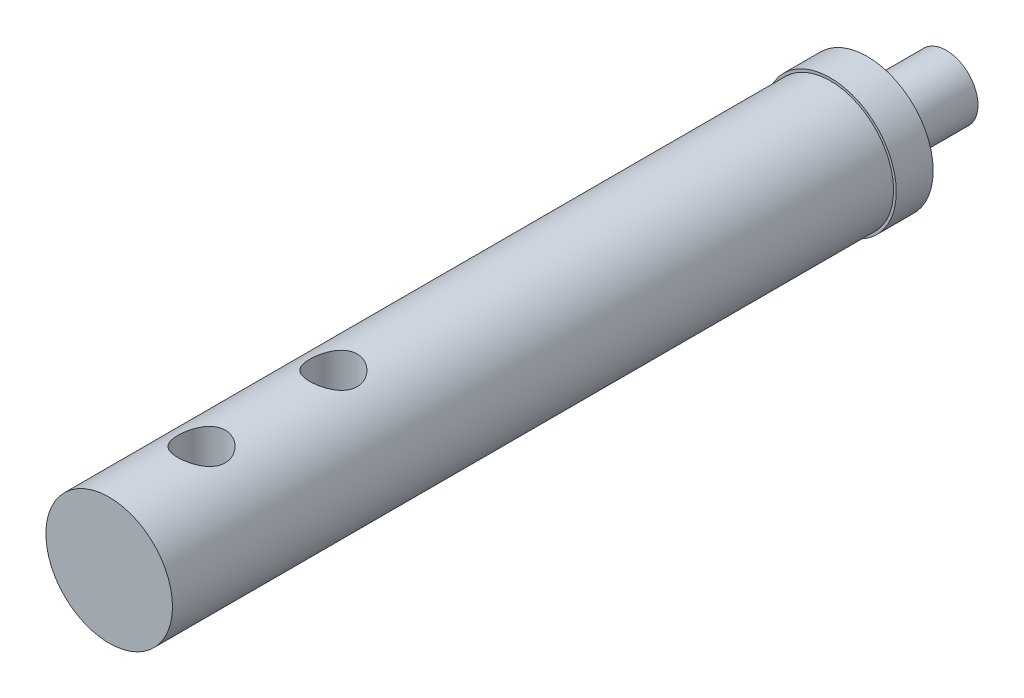
SolidWorks part; units mm, degrees
material "Galvanized Steel"
ref_plane "Front Plane" through (0, 0, 0) normal (0, 0, 1) x (1, 0, 0)
ref_plane "Top Plane" through (0, 0, 0) normal (0, 1, 0) x (1, 0, 0)
ref_plane "Right Plane" through (0, 0, 0) normal (1, 0, 0) x (0, 0, -1)
sketch "Sketch1" plane through (0, 0, 0) normal (0, 0, 1) x (1, 0, 0)
  circle A0 centre (0, 0) radius 6
  dimension "D1" = 12
extrude "Boss-Extrude1" add sketch "Sketch1" along normal blind 15
sketch "Sketch2" plane through (0, 0, 15) normal (0, 0, 1) x (1, 0, 0)
  circle A0 centre (0, 0) radius 12.5
  dimension "D1" = 25
extrude "Boss-Extrude2" add sketch "Sketch2" along normal blind 7
sketch "Sketch3" plane through (0, 0, 22) normal (0, 0, 1) x (1, 0, 0)
  circle A0 centre (0, 0) radius 12
  dimension "D1" = 24
extrude "Boss-Extrude3" add sketch "Sketch3" along normal blind 136.7
sketch "Sketch4" plane through (0, 0, 0) normal (0, 1, 0) x (1, 0, 0)
  line L0 (-12, -158.7) -> (12, -158.7) construction
  circle A0 centre (0, -141.2) radius 4.5
  dimension "D1" = 9
  dimension "D2" = 17.5
extrude "Cut-Extrude1" cut sketch "Sketch4" against normal through all both and the other way through all
pattern_linear "LPattern1" count 2 spacing 25 along (0, 0, -1) of "Cut-Extrude1"
